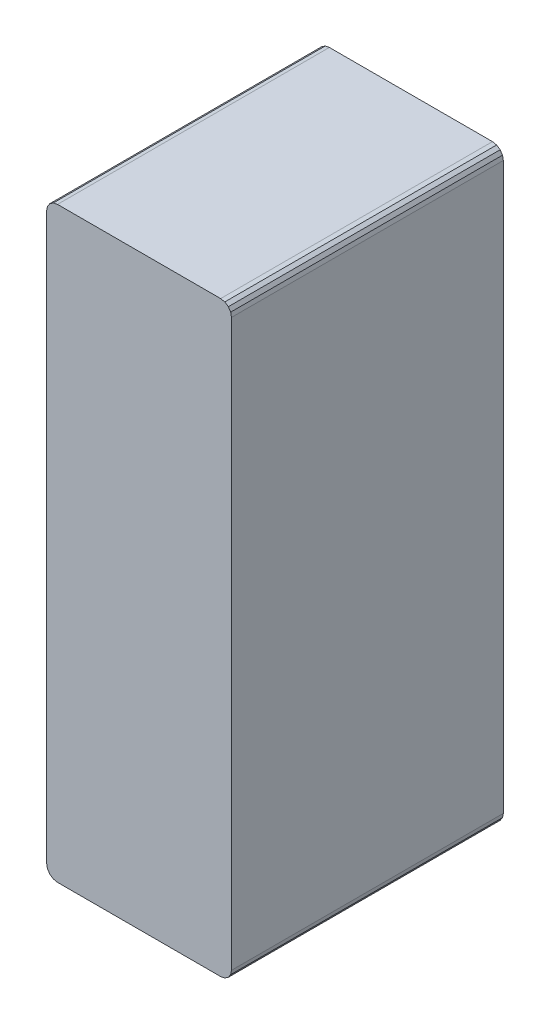
SolidWorks part; units mm, degrees
ref_plane "前视基准面" through (0, 0, 0) normal (0, 0, 1) x (1, 0, 0)
ref_plane "上视基准面" through (0, 0, 0) normal (0, 1, 0) x (1, 0, 0)
ref_plane "右视基准面" through (0, 0, 0) normal (1, 0, 0) x (0, 0, -1)
other "Configuration Table"
sketch "S01_圆角包络轮廓" plane through (0, 0, 0) normal (0, 0, 1) x (1, 0, 0)
  line L0 (17, 52) -> (16.8478, 52.7654)
  line L1 (16.8478, 52.7654) -> (16.4142, 53.4142)
  line L2 (16.4142, 53.4142) -> (15.7654, 53.8478)
  line L3 (15.7654, 53.8478) -> (15, 54)
  line L4 (15, 54) -> (-15, 54)
  line L5 (-15, 54) -> (-15.7654, 53.8478)
  line L6 (-15.7654, 53.8478) -> (-16.4142, 53.4142)
  line L7 (-16.4142, 53.4142) -> (-16.8478, 52.7654)
  line L8 (-16.8478, 52.7654) -> (-17, 52)
  line L9 (-17, 52) -> (-17, -52)
  line L10 (-17, -52) -> (-16.8478, -52.7654)
  line L11 (-16.8478, -52.7654) -> (-16.4142, -53.4142)
  line L12 (-16.4142, -53.4142) -> (-15.7654, -53.8478)
  line L13 (-15.7654, -53.8478) -> (-15, -54)
  line L14 (-15, -54) -> (15, -54)
  line L15 (15, -54) -> (15.7654, -53.8478)
  line L16 (15.7654, -53.8478) -> (16.4142, -53.4142)
  line L17 (16.4142, -53.4142) -> (16.8478, -52.7654)
  line L18 (16.8478, -52.7654) -> (17, -52)
  line L19 (17, -52) -> (17, 52)
  point P0 (0, 0)
  dimension "D1" = 0.1522
  dimension "D2" = 0.5858
  dimension "D3" = 1.2346
  dimension "D4" = 2
  dimension "D5" = 17
  dimension "D6" = 32
  dimension "D7" = 32.7654
  dimension "D8" = 33.4142
  dimension "D9" = 33.8478
  dimension "D10" = 34
  dimension "D11" = 0.1522
  dimension "D12" = 0.5858
  dimension "D13" = 1.2346
  dimension "D14" = 2
  dimension "D15" = 54
  dimension "D16" = 106
  dimension "D17" = 106.7654
  dimension "D18" = 107.4142
  dimension "D19" = 107.8478
  dimension "D20" = 108
extrude "B01_圆角包络轮廓" add sketch "S01_圆角包络轮廓" along normal blind 50 from offset 0
